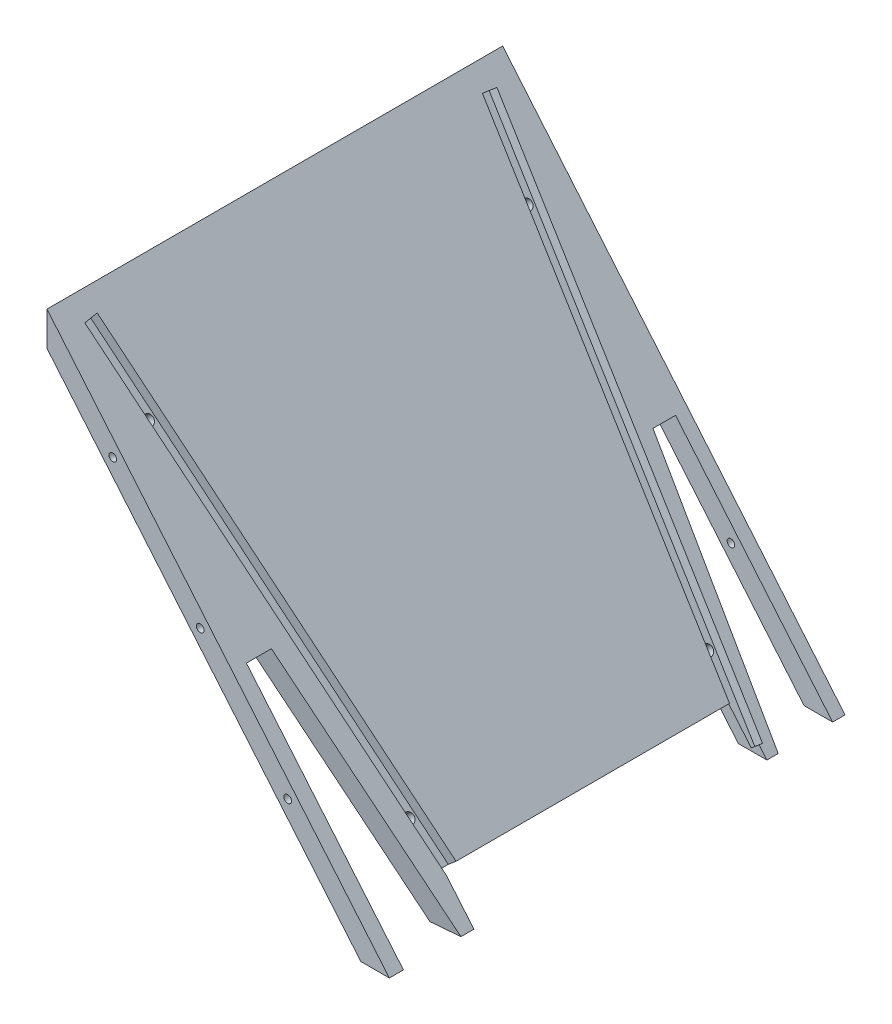
SolidWorks part; units mm, degrees
ref_plane "Front Plane" through (0, 0, 0) normal (0, 0, 1) x (1, 0, 0)
ref_plane "Top Plane" through (0, 0, 0) normal (0, 1, 0) x (1, 0, 0)
ref_plane "Right Plane" through (0, 0, 0) normal (1, 0, 0) x (0, 0, -1)
sketch "Sketch1" plane through (0, 0, 0) normal (0, 0, 1) x (1, 0, 0)
  line L0 (0, 0) -> (127.8788, 0)
  line L1 (127.8788, 0) -> (0, 152.4)
  line L2 (0, 152.4) -> (0, 0)
  line L3 (0, 152.4) -> (0, 139.7)
  line L4 (0, 139.7) -> (117.2222, 0)
  line L5 (117.2222, 0) -> (127.8788, 0)
  dimension "D1" = 50
  dimension "D2" = 152.4
  dimension "D3" = 12.7
extrude "Boss-Extrude1" add sketch "Sketch1" along normal blind 170.18 contours L2 L4 L0 L1
sketch "Sketch2" plane through (75.0424, 62.968, 0) normal (0.766, 0.6428, 0) x (0, 0, -1)
  line L0 (-137.16, -77.2613) -> (-161.29, 108.5547)
  line L2 (-33.02, -77.2613) -> (-12.8138, 108.5547)
  line L3 (-170.18, -82.1989) -> (-170.18, 116.7452) construction
  line L4 (0, -82.1989) -> (0, 116.7452) construction
  dimension "D1" = 104.14
  dimension "D3" = 33.02
  dimension "D4" = 33.02
  dimension "D5" = 8.89
extrude "Cut-Extrude-Thin2" cut sketch "Sketch2" against normal blind 3.81 thin
sketch "Sketch3" plane through (75.0424, 62.968, 0) normal (0.766, 0.6428, 0) x (0, 0, -1)
  line L0 (-164.9266, 9.0381) -> (-164.9266, -99.7204)
  line L1 (-164.9266, -99.7204) -> (-141.1263, -99.7204)
  line L2 (-141.1263, -99.7204) -> (-155.5872, 9.0381)
  line L3 (-155.5872, 9.0381) -> (-164.9266, 9.0381)
  line L4 (-13.0864, 9.0381) -> (-27.2461, -99.7204)
  line L5 (-27.2461, -99.7204) -> (-4.6508, -99.7204)
  line L6 (-4.6508, -99.7204) -> (-4.6508, 9.0381)
  line L7 (-4.6508, 9.0381) -> (-13.0864, 9.0381)
extrude "Cut-Extrude1" cut sketch "Sketch3" against normal blind 25.4
sketch "Sketch4" plane through (0, 0, 170.18) normal (0, 0, 1) x (1, 0, 0)
  line L0 (0, 146.05) -> (122.5505, 0) construction
  line L1 (0, 152.4) -> (0, 139.7) construction
  line L2 (117.2222, 0) -> (127.8788, 0) construction
  circle A0 centre (24.5897, 116.7452) radius 1.4224
  circle A1 centre (57.2433, 77.8301) radius 1.4224
  circle A2 centre (89.8969, 38.9151) radius 1.4224
  dimension "D1" = 50.8
  dimension "D2" = 50.8
  dimension "D3" = 50.8
extrude "Cut-Extrude2" cut sketch "Sketch4" against normal blind 10.16
ref_plane "Plane1" through (0, 0, 85.09) normal (0, 0, 1) x (1, 0, 0)
mirror "Mirror1" about plane through (0, 0, 85.09) normal (0, 0, 1) of "Cut-Extrude2"
sketch "Sketch5" plane through (75.0424, 62.968, 0) normal (0.766, 0.6428, 0) x (0, 0, -1)
  line L0 (-143.456, -82.1989) -> (-24.9649, -82.1989) construction
  line L1 (-138.6025, -82.1989) -> (-29.1992, -82.1989)
  line L2 (-138.6025, -82.1989) -> (-138.6025, -64.2508)
  line L3 (-138.6025, -64.2508) -> (-29.1992, -64.2508)
  line L4 (-29.1992, -82.1989) -> (-29.1992, -64.2508)
extrude "Cut-Extrude3" cut sketch "Sketch5" against normal blind 12.7
sketch "Sketch6" plane through (72.1237, 60.519, 0) normal (0.766, 0.6428, 0) x (0, 0, -1)
  line L0 (-158.7711, 108.8818) -> (-136.0536, -66.0571) construction
  line L1 (-161.29, 108.5547) -> (-156.2523, 109.2089) construction
  line L2 (-133.4556, -66.3396) -> (-138.6517, -65.7746) construction
  line L3 (-10.2887, 108.2801) -> (-30.4734, -77.4455) construction
  line L4 (-12.8138, 108.5547) -> (-7.7636, 108.0055) construction
  circle A0 centre (-154.6824, 77.3961) radius 1.905
  circle A1 centre (-138.3276, -48.5464) radius 1.905
  circle A2 centre (-13.7191, 76.7159) radius 1.905
  circle A3 centre (-27.4407, -49.5406) radius 1.905
  point P14 (-30.4734, -77.4455)
  point P20 (0, 0)
  point P21 (0, 0)
  point P22 (-28.5845, -77.7436)
  dimension "D1" = 127
  dimension "D2" = 127
  dimension "D3" = 31.75
  dimension "D4" = 31.75
extrude "Cut-Extrude4" cut sketch "Sketch6" against normal blind 12.7
